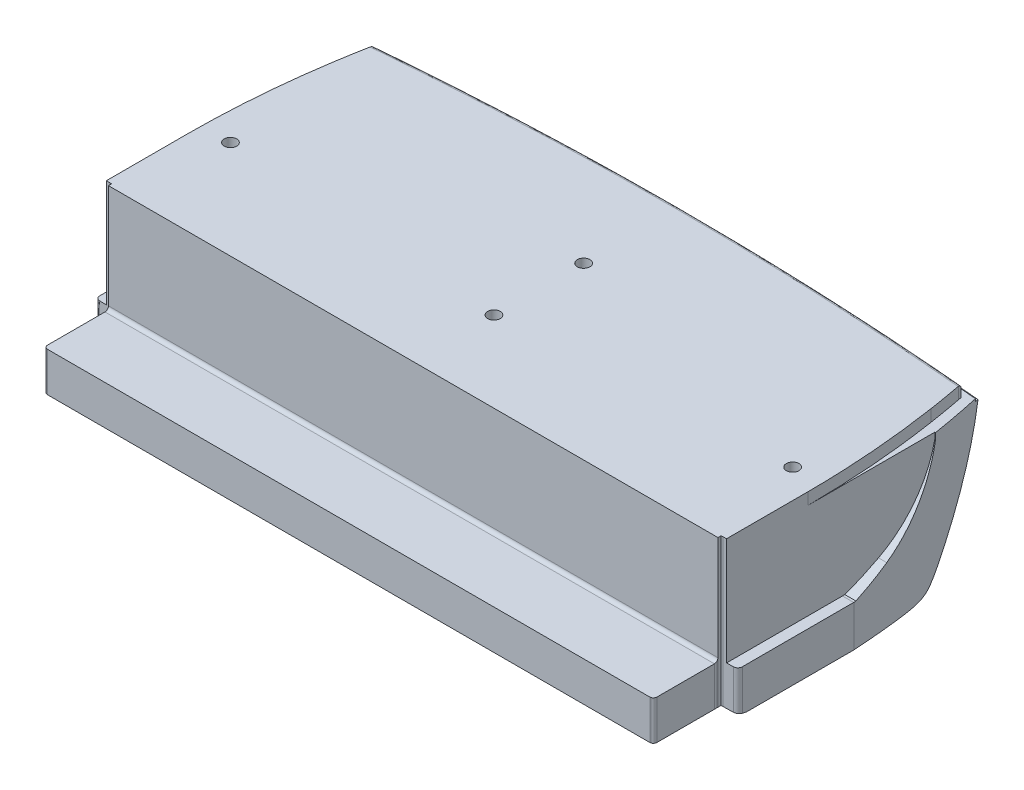
SolidWorks part; units mm, degrees
ref_plane "Front Plane" through (0, 0, 0) normal (0, 0, 1) x (1, 0, 0)
ref_plane "Top Plane" through (0, 0, 0) normal (0, 1, 0) x (1, 0, 0)
ref_plane "Right Plane" through (0, 0, 0) normal (1, 0, 0) x (0, 0, -1)
sketch "Sketch1" plane through (0, 0, 0) normal (0, 1, 0) x (1, 0, 0)
  line L0 (-207.6994, -36.2628) -> (-201.8592, -36.3648)
  line L1 (-200.9091, -38.1123) -> (-200.9091, -37.3461)
  line L2 (-200.9091, -38.1123) -> (-200.9174, -38.7893)
  line L3 (-200.9174, -38.7893) -> (-200.9178, -40.112)
  line L4 (-200.9178, -72.2053) -> (-200.9178, -40.112)
  line L5 (-198.9135, -74.2137) -> (137.4927, -74.2137)
  line L6 (139.4953, -40.1121) -> (139.4953, -72.2052)
  line L7 (139.4953, -40.1121) -> (139.4945, -38.7892)
  line L8 (139.4945, -38.7892) -> (139.4866, -38.1123)
  line L9 (139.4866, -38.1123) -> (139.4866, -37.3433)
  line L10 (-201.8592, -36.3648) -> (-200.9091, -36.3648)
  line L11 (140.4369, -36.3646) -> (146.2773, -36.2626)
  line L12 (-210.1542, 28.6685) -> (-210.1542, -33.7632)
  line L13 (148.7321, -33.763) -> (148.7321, 28.6645)
  line L14 (-200.9091, -37.3461) -> (-200.9091, -36.3648)
  line L15 (140.4369, -36.3646) -> (139.4866, -36.3646)
  line L16 (139.4866, -37.3433) -> (139.4866, -36.3646)
  line L17 (-55, 0) -> (55, 0) construction
  arc A1 (137.2411, 109.432) -> (148.7321, 28.6645) centre (-380.1778, -5.3837) cw
  arc A2 (-198.6637, 109.432) -> (-210.1542, 28.6685) centre (318.3378, -5.3229) ccw
  ellipse E1 centre (-198.9075, -72.2046) end of major axis (-200.3292, -73.6264) minor radius 2.01 (-200.9178, -72.2053) -> (-199.4176, -74.1493) ccw
  ellipse E2 centre (-198.9162, -72.2079) end of major axis (-197.497, -73.6272) minor radius 2.0044 (-199.4176, -74.1493) -> (-198.9135, -74.2137) ccw
  ellipse E3 centre (137.494, -72.2077) end of major axis (138.9136, -70.7881) minor radius 2.0043 (137.4927, -74.2137) -> (137.9951, -74.1492) ccw
  ellipse E4 centre (137.485, -72.2046) end of major axis (138.9067, -73.6263) minor radius 2.01 (137.9951, -74.1492) -> (139.4953, -72.2052) ccw
  parabola Q1 (137.2411, 109.432) -> (-30.7113, 116.9355) focus (454.0207, -518.12) apex (760.307, -116.8514)
  parabola Q2 (-30.7113, 116.9355) -> (-198.6637, 109.432) focus (-515.4427, -518.1216) apex (-821.7295, -116.8507)
  spline S0 degree 3 poles (-210.1542, -33.7632) (-210.1532, -33.8184) (-210.1511, -33.9263) (-210.1351, -34.0839) (-210.1112, -34.2329) (-210.0801, -34.373) (-210.0432, -34.5037) (-210.0024, -34.6252) (-209.9711, -34.7019) (-209.956, -34.7391) knots 0 0 0 0 0.165026 0.322945 0.473512 0.616561 0.752 0.879802 1 1 1 1
  spline S1 degree 3 poles (-209.956, -34.7391) (-209.9337, -34.789) (-209.8903, -34.8863) (-209.8155, -35.0229) (-209.7376, -35.148) (-209.657, -35.2619) (-209.5191, -35.4362) (-209.3135, -35.6461) (-209.0157, -35.8708) (-208.7012, -36.0434) (-208.4069, -36.1535) (-208.1504, -36.2168) (-207.9287, -36.2527) (-207.7771, -36.2594) (-207.6994, -36.2628) knots 0 0 0 0 0.056912 0.11093 0.162105 0.210515 0.256258 0.393682 0.515355 0.643842 0.766318 0.841826 0.918989 1 1 1 1
  spline S2 degree 3 poles (146.2773, -36.2626) (146.3315, -36.2607) (146.4436, -36.2566) (146.6163, -36.2355) (146.7989, -36.2008) (146.9907, -36.1484) (147.2621, -36.0499) (147.6242, -35.8606) (147.9972, -35.5565) (148.3299, -35.1546) (148.5361, -34.7676) (148.6448, -34.4327) (148.6968, -34.1986) (148.7265, -33.9877) (148.7303, -33.8342) (148.7321, -33.763) knots 0 0 0 0 0.041986 0.086722 0.134525 0.185675 0.240412 0.357707 0.50003 0.609523 0.759628 0.835708 0.881296 0.944991 1 1 1 1
extrude "Extrude1" add sketch "Sketch1" along normal blind 83.1088
sketch "Sketch2" plane through (0, 0, 0) normal (1, 0, 0) x (0, 0, -1)
  line L0 (-40.1121, 83.1088) -> (-40.1121, 0) construction
  line L1 (-74.2137, 22.9985) -> (-74.2137, 1)
  line L2 (-40.1122, 22.9985) -> (-74.2137, 22.9985)
  line L3 (-74.2137, 83.1088) -> (-74.2137, 0) construction
  line L4 (-38.1456, 24.9649) -> (-38.1456, 83.1088)
  line L5 (-137.0818, 122.9193) -> (197.5519, 122.9193)
  line L9 (-31.5173, 0) -> (116.9355, 0)
  line L10 (-38.1456, 83.1088) -> (116.9355, 83.1088)
  line L11 (-137.0818, 122.9193) -> (-137.0818, -49.2675)
  line L12 (-137.0818, -49.2675) -> (197.5519, -49.2675)
  line L13 (116.9355, 0) -> (116.9355, 83.1088)
  line L21 (-36.0173, 1) -> (-31.5173, 0)
  line L22 (-74.2137, 1) -> (-36.0173, 1)
  line L25 (197.5519, 122.9193) -> (197.5519, -49.2675)
  arc A0 (-40.1122, 22.9985) -> (-38.1456, 24.9649) centre (-40.1121, 24.965) ccw
extrude "Extrude6" cut sketch "Sketch2" against normal mid plane 508
sketch "Sketch5" plane through (0, 83.1088, -233.8759) normal (0, -1, 0) x (1, 0, 0)
  line L0 (-30.7113, -215.3506) -> (-30.7113, 116.9404) construction
  arc A0 (-198.6637, 109.4435) -> (-30.7113, 116.9404) centre (-30.7113, -1768.1179) cw
ref_plane "Plane1" through (-30.7113, 0, 0) normal (1, 0, 0) x (0, 0, -1)
ref_plane "Plane2" through (0, 0, 1768.1194) normal (0, 0, 1) x (1, 0, 0)
ref_axis "Axis1" through (-30.7113, -6.8336, 1768.1194) along (0, 1, 0)
sketch "Sketch4" plane through (-30.7113, 0, 0) normal (1, 0, 0) x (0, 0, -1)
  line L2 (60.8871, 0.0057) -> (60.8871, -17.5415)
  line L3 (109.1953, 83.1083) -> (-52.0481, 83.1083)
  line L4 (115.0884, 76.5085) -> (111.3168, 76.5085)
  line L5 (116.8462, 75.0085) -> (114.9572, 75.0086)
  line L6 (111.3168, 76.5085) -> (111.1947, 81.1608)
  line L7 (114.9703, 75.1585) -> (115.0884, 76.5085)
  line L11 (114.9703, 75.1585) -> (114.9572, 75.0086)
  line L12 (-52.0481, 83.1083) -> (-52.0481, 90.1112)
  line L13 (-52.0481, 90.1112) -> (128.1588, 90.1112)
  line L14 (128.1588, 90.1112) -> (128.1588, -17.5415)
  line L15 (128.1588, -17.5415) -> (60.8871, -17.5415)
  arc A0 (116.8462, 75.0085) -> (108.5899, 47.1731) centre (-27.5912, 102.7079) cw
  spline S4 degree 3 poles (108.5899, 47.1731) (104.6445, 37.6375) (99.9867, 28.3973) (94.6678, 19.554) knots 0 0 0 0 1 1 1 1
  spline S5 degree 3 poles (94.6678, 19.554) (94.171, 18.734) (93.6772, 17.9244) (92.6966, 16.3299) (92.2097, 15.5451) (91.2355, 13.9912) (90.7492, 13.2222) (89.7697, 11.6965) (89.2748, 10.938) (88.2673, 9.4481) (87.755, 8.7184) (86.7124, 7.3068) (86.1823, 6.624) (85.0732, 5.3122) (84.4899, 4.6813) (83.2249, 3.5138) (82.5455, 2.9804) (81.0731, 2.0865) (80.2751, 1.7307) (78.6471, 1.1725) (77.8186, 0.9681) (76.1646, 0.6492) (75.3327, 0.5323) (73.6338, 0.344) (72.7641, 0.2738) (70.9985, 0.1687) (70.1041, 0.1342) (68.3088, 0.0823) (67.4062, 0.0644) (65.5824, 0.0341) (64.662, 0.0231) (62.7952, 0.0088) (61.8477, 0.0055) (60.8871, 0.0057) knots 0 0 0 0 0.0625 0.0625 0.125 0.125 0.1875 0.1875 0.25 0.25 0.3125 0.3125 0.375 0.375 0.4375 0.4375 0.5 0.5 0.5625 0.5625 0.625 0.625 0.6875 0.6875 0.75 0.75 0.8125 0.8125 0.875 0.875 0.9375 0.9375 1 1 1 1
  spline S6 degree 3 poles (111.1947, 81.1608) (111.1926, 81.2056) (111.1886, 81.2947) (111.1713, 81.4263) (111.1464, 81.5545) (111.1139, 81.6781) (111.0747, 81.7964) (111.0296, 81.9087) (110.9796, 82.0144) (110.9257, 82.1133) (110.869, 82.2051) (110.8103, 82.2896) (110.7506, 82.3671) (110.6907, 82.4376) (110.6314, 82.5013) (110.5735, 82.5585) (110.5175, 82.6096) (110.464, 82.655) (110.4135, 82.695) (110.3656, 82.7306) (110.3189, 82.7633) (110.272, 82.7941) (110.2242, 82.8237) (110.1755, 82.8521) (110.1258, 82.879) (110.0754, 82.9046) (110.0242, 82.9288) (109.9723, 82.9515) (109.9198, 82.9728) (109.8668, 82.9926) (109.753, 83.0313) (109.5793, 83.0761) (109.4015, 83.0996) (109.2875, 83.1065) (109.2453, 83.1078) (109.2187, 83.1082) (109.2061, 83.1083) (109.1991, 83.1083) (109.1969, 83.1083) (109.1953, 83.1083) knots 0 0 0 0 0.043404 0.086266 0.128412 0.16968 0.209916 0.248977 0.286736 0.323079 0.357909 0.391141 0.422706 0.45255 0.480628 0.50691 0.531372 0.554001 0.574789 0.593735 0.611786 0.629893 0.648047 0.666242 0.684469 0.70272 0.720987 0.739262 0.757537 0.775803 0.794054 0.873892 0.949052 0.9669 0.984842 0.989268 0.993555 0.995407 1 1 1 1
revolve "Cut-Revolve10" cut sketch "Sketch4" angle 360 about axis through (-30.7113, -6.8336, 1768.1194) along (0, 1, 0)
ref_plane "Plane3" through (-203.9058, 0, 0) normal (-1, 0, 0) x (0, 0, 1)
sketch "Sketch8" plane through (-203.9058, 0, 0) normal (-1, 0, 0) x (0, 0, 1)
  line L0 (-29.7567, 23.0472) -> (-28.4268, 23.0427)
  line L1 (-28.4268, 23.0427) -> (119.7675, 22.9999)
  line L3 (-80.067, 73.4038) -> (-80.067, 102.6142)
  line L4 (-80.067, 102.6142) -> (119.7675, 102.6142)
  line L5 (119.7675, 102.6142) -> (119.7675, 22.9999)
  spline S0 degree 3 poles (-48.5588, 31.4119) (-48.118, 31.1827) (-47.2415, 30.7269) (-45.9263, 30.0622) (-44.6206, 29.416) (-43.3241, 28.7891) (-42.0374, 28.1808) (-40.7607, 27.5909) (-39.4942, 27.0189) (-38.2382, 26.4645) (-36.9931, 25.9274) (-35.759, 25.4072) (-34.5361, 24.9035) (-33.3249, 24.4161) (-32.1253, 23.9446) (-30.938, 23.4881) (-30.1487, 23.1935) (-29.7567, 23.0472) knots 0 0 0 0 0.072407 0.143993 0.21476 0.284707 0.353834 0.422141 0.489628 0.556295 0.622141 0.687168 0.751375 0.814761 0.877328 0.939074 1 1 1 1
  spline S1 degree 3 poles (-80.067, 73.4038) (-79.9123, 72.6768) (-79.6019, 71.218) (-79.0332, 69.0465) (-78.3866, 66.8824) (-77.654, 64.7307) (-76.8369, 62.5944) (-75.3672, 59.1463) (-72.9365, 54.435) (-69.2102, 48.8399) (-64.8131, 43.5974) (-61.3065, 40.2548) (-59.0358, 38.3561) (-58.3037, 37.7627) (-57.5472, 37.1688) (-56.7656, 36.5752) (-55.9588, 35.9828) (-55.1263, 35.3925) (-54.2678, 34.8054) (-53.383, 34.2223) (-52.4716, 33.6444) (-51.5333, 33.0726) (-50.5677, 32.5084) (-49.5755, 31.9513) (-48.8996, 31.5927) (-48.5588, 31.4119) knots 0 0 0 0 0.040974 0.082211 0.123714 0.165484 0.207525 0.249838 0.372237 0.499507 0.620486 0.75006 0.767104 0.784511 0.802281 0.820416 0.838914 0.857776 0.877001 0.896591 0.916545 0.936862 0.957544 0.97859 1 1 1 1
extrude "Extrude10" cut sketch "Sketch8" along normal blind 17.78
mirror "Mirror1" about plane through (-30.7113, 0, 0) normal (1, 0, 0) of "Extrude10"
sketch "Sketch9" plane through (0, 76.5085, 0.0047) normal (0, 1, 0) x (1, 0, 0)
  line L0 (-203.9058, 5.9511) -> (-212.7118, 5.9511)
  line L3 (-212.7118, 5.9511) -> (-212.7118, 157.0219)
  line L4 (-212.7118, 157.0219) -> (158.3907, 157.0219)
  line L5 (158.3907, 157.0219) -> (158.3907, 5.9574)
  line L8 (-203.9058, 80.0717) -> (-203.9058, -36.3244) construction
  line L9 (142.4832, -36.3242) -> (142.4832, 80.0717) construction
  line L14 (129.6521, 120.1181) -> (-188.9569, 129.0323)
  line L15 (142.4832, 5.9574) -> (158.3907, 5.9574)
  arc A0 (136.6801, 83.5797) -> (133.4256, 102.3504) centre (-357.5142, 7.5631) ccw
  arc A1 (-194.8482, 102.3504) -> (-188.9569, 129.0323) centre (302.5733, 6.512) cw
  arc A2 (-198.0899, 83.663) -> (-203.9058, 5.9511) centre (296.0915, 7.6051) ccw
  arc A3 (133.4256, 102.3504) -> (129.6521, 120.1181) centre (-347.3405, 9.5273) ccw
  spline S1 degree 3 poles (-194.8482, 102.3504) (-196.0468, 96.1425) (-197.1276, 89.9119) (-198.0899, 83.663) knots 0 0 0 0 1 1 1 1
  spline S2 degree 3 poles (142.4832, 5.9574) (142.5688, 31.9299) (140.6266, 57.9087) (136.6801, 83.5797) knots 0 0 0 0 1 1 1 1
  point P0 (-30.7058, 143.0259)
extrude "Extrude16" cut sketch "Sketch9" along normal blind 6.604
sketch "Sketch10" plane through (0, 83.1083, 0) normal (0, 1, 0) x (1, 0, 0)
  line L2 (-185.1033, -74.2137) -> (122.7789, -74.2137) construction
  circle A0 centre (-187.7113, 16.7798) radius 3.5098
  circle A1 centre (-30.7113, 57.0398) radius 3.5092
  circle A2 centre (-30.7113, 6.9398) radius 3.5092
  circle A3 centre (126.2887, 16.7798) radius 3.5098
extrude "Extrude17" cut sketch "Sketch10" against normal blind 176.276
sketch "Sketch11" [suppressed] plane through (0, 0, 74.2137) normal (0, 0, 1) x (1, 0, 0)
  line L1 (-260.0795, 58.7706) -> (242.7778, 58.7706)
  line L2 (-260.0795, 58.7706) -> (-260.0795, -31.8121)
  line L3 (-260.0795, -31.8121) -> (242.7778, -31.8121)
  line L4 (242.7778, 58.7706) -> (242.7778, -31.8121)
extrude "Extrude18" [suppressed] cut sketch "Sketch11" against normal up to surface (36.0681 mm away)
